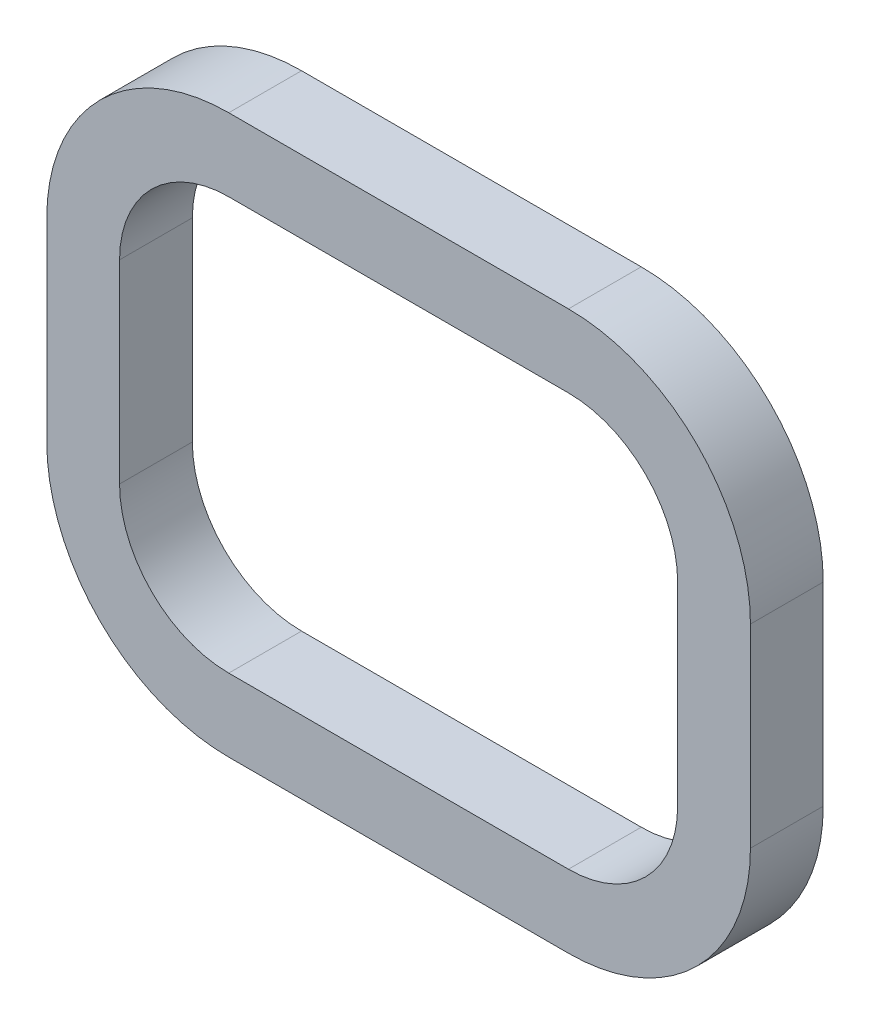
SolidWorks part; units mm, degrees
ref_plane "Front" through (0, 0, 0) normal (0, 0, 1) x (1, 0, 0)
ref_plane "Top" through (0, 0, 0) normal (0, 1, 0) x (1, 0, 0)
ref_plane "Right" through (0, 0, 0) normal (1, 0, 0) x (0, 0, -1)
sketch "Sketch1" plane through (0, 0, 0) normal (0, 0, 1) x (1, 0, 0)
  line L1 (-35, 50) -> (35, 50)
  line L2 (-65, 20) -> (-65, -20)
  line L3 (-35, -50) -> (35, -50)
  line L4 (65, 20) -> (65, -20)
  line L5 (-65, 50) -> (65, -50) construction
  line L6 (-65, -50) -> (65, 50) construction
  arc A0 (35, 50) -> (65, 20) centre (35, 20) cw
  arc A1 (35, -50) -> (65, -20) centre (35, -20) ccw
  arc A2 (-65, -20) -> (-35, -50) centre (-35, -20) ccw
  arc A3 (-35, 50) -> (-65, 20) centre (-35, 20) ccw
  point P0 (0, 0)
  dimension "D3" = 30
  dimension "D1" = 130
  dimension "D2" = 100
extrude "Extrude-Thin1" add sketch "Sketch1" along normal mid plane 15 thin thin type mid plane wall 15
sketch "Cable Pocket Guide" plane through (0, 0, 0) normal (0, 0, 1) x (1, 0, 0)
  line L0 (-57.5, 20) -> (-57.5, -20) construction
  line L1 (-35, -42.5) -> (35, -42.5) construction
  line L2 (57.5, -20) -> (57.5, 20) construction
  line L3 (35, 42.5) -> (-35, 42.5) construction
  line L4 (-57.5, 20) -> (-57.5, -20)
  line L5 (-35, -42.5) -> (35, -42.5)
  line L6 (57.5, -20) -> (57.5, 20)
  line L7 (35, 42.5) -> (-35, 42.5)
  arc A0 (-35, 42.5) -> (-57.5, 20) centre (-35, 20) ccw construction
  arc A1 (-57.5, -20) -> (-35, -42.5) centre (-35, -20) ccw construction
  arc A2 (35, -42.5) -> (57.5, -20) centre (35, -20) ccw construction
  arc A3 (57.5, 20) -> (35, 42.5) centre (35, 20) ccw construction
  arc A4 (-35, 42.5) -> (-57.5, 20) centre (-35, 20) ccw
  arc A5 (-57.5, -20) -> (-35, -42.5) centre (-35, -20) ccw
  arc A6 (35, -42.5) -> (57.5, -20) centre (35, -20) ccw
  arc A7 (57.5, 20) -> (35, 42.5) centre (35, 20) ccw
